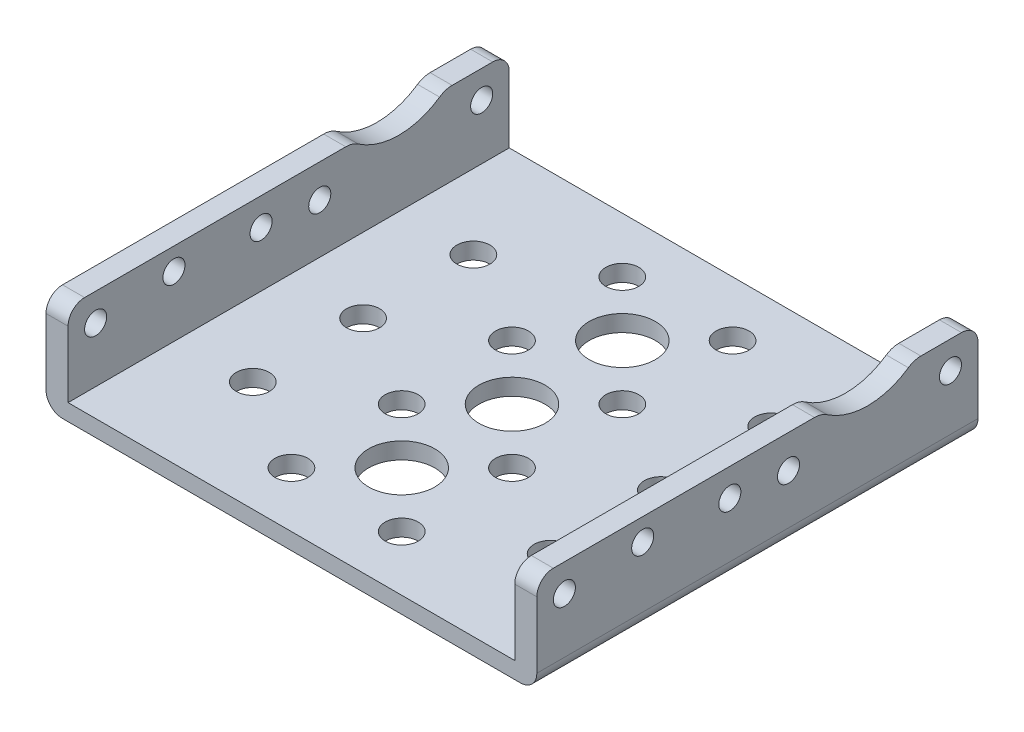
SolidWorks part; units mm, degrees
ref_plane "前视基准面" through (0, 0, 0) normal (0, 0, 1) x (1, 0, 0)
ref_plane "上视基准面" through (0, 0, 0) normal (0, 1, 0) x (1, 0, 0)
ref_plane "右视基准面" through (0, 0, 0) normal (1, 0, 0) x (0, 0, -1)
other "Configuration Table"
ref_plane "基准面1" through (0, 9, 0) normal (0, 1, 0) x (1, 0, 0)
sketch "草图1" plane through (0, 9, 0) normal (0, 1, 0) x (1, 0, 0)
  line L0 (-22.25, -20) -> (22.25, -20)
  line L1 (22.25, -20) -> (22.25, 20)
  line L2 (22.25, 20) -> (-22.25, 20)
  line L3 (-22.25, 20) -> (-22.25, -20)
  line L4 (22.25, 20) -> (-22.25, -20) construction
  line L5 (22.25, -20) -> (-22.25, 20) construction
  point P4 (0, 0)
  dimension "D1" = 44.5
  dimension "D2" = 40
extrude "凸台-拉伸1" add sketch "草图1" against normal blind 9
sketch "草图2" plane through (0, 0, -20) normal (0, 0, -1) x (-1, 0, 0)
  line L0 (20.25, 9) -> (-20.25, 9)
  line L1 (-20.25, 9) -> (-20.25, 1.5)
  line L2 (-20.25, 1.5) -> (20.25, 1.5)
  line L3 (20.25, 1.5) -> (20.25, 9)
extrude "切除-拉伸1" cut sketch "草图2" against normal through all
sketch "草图3" plane through (22.25, 0, 0) normal (1, 0, 0) x (0, 0, -1)
  line L0 (14.1533, 9) -> (5.8467, 9)
  arc A0 (5.8467, 9) -> (14.1533, 9) centre (10, 14) ccw
extrude "切除-拉伸2" cut sketch "草图3" against normal up to next
sketch "草图4" plane through (-22.25, 0, 0) normal (-1, 0, 0) x (0, 0, 1)
  line L0 (-5.8467, 9) -> (-14.1533, 9)
  arc A0 (-14.1533, 9) -> (-5.8467, 9) centre (-10, 14) ccw
extrude "切除-拉伸3" cut sketch "草图4" against normal through all
hole_wizard "Ø6.0 (6) 直径孔1" positions "草图6" profile "草图5" hole size "Ø6.0" standard "ANSI Metric"
sketch "草图6" plane through (0, 0, 0) normal (0, -1, 0) x (-1, 0, 0)
  point P0 (0, 0)
  point P1 (0, 10)
  point P2 (0, -10)
sketch "草图5" plane through (0, 0, 0) normal (1, 0, 0) x (0, 0, -1)
  line L0 (0, 0) -> (0, 9)
  line L1 (0, 9) -> (3, 9)
  line L2 (3, 9) -> (3, 0)
  line L5 (3, 0) -> (0, 0)
  line L11 (0, -6.35) -> (0, 107.95) construction
  dimension "通孔孔直径" = 6
  dimension "通孔孔深度" = 9
hole_wizard "Ø3.0 (3) 直径孔1" positions "草图8" profile "草图7" hole size "Ø3.0" standard "ANSI Metric"
sketch "草图8" plane through (0, 0, 0) normal (0, -1, 0) x (-1, 0, 0)
  point P0 (5, 5)
  point P1 (-5, 5)
  point P2 (-5, -5)
  point P3 (5, -5)
  point P4 (5, 15)
  point P5 (-5, 15)
  point P6 (-5, -15)
  point P7 (5, -15)
  point P8 (13.5, 10)
  point P9 (13.5, 0)
  point P10 (13.5, -10)
  point P11 (-13.5, 10)
  point P12 (-13.5, 0)
  point P13 (-13.5, -10)
  point P15 (0, 0)
  point P16 (0, 0)
  point P17 (0, 0)
  dimension "D1" = 13.5
  dimension "D2" = 13.5
  dimension "D3" = 10
  dimension "D4" = 10
sketch "草图7" plane through (-5, 0, -5) normal (1, 0, 0) x (0, 0, -1)
  line L0 (0, 0) -> (0, 9)
  line L1 (0, 9) -> (1.5, 9)
  line L2 (1.5, 9) -> (1.5, 0)
  line L5 (1.5, 0) -> (0, 0)
  line L11 (0, -6.35) -> (0, 107.95) construction
  dimension "通孔孔直径" = 3
  dimension "通孔孔深度" = 9
hole_wizard "Ø2.0 (2) 直径孔1" positions "草图10" profile "草图9" hole size "Ø2.0" standard "ANSI Metric"
sketch "草图10" plane through (-22.25, 0, 0) normal (-1, 0, 0) x (0, 0, 1)
  point P0 (-17.5, 6.5)
  point P1 (2.5, 6.5)
  point P2 (10.4, 7)
  point P3 (17.5, 6.5)
  point P4 (-2.82, 6)
sketch "草图9" plane through (-22.25, 6.5, -17.5) normal (0, 1, 0) x (0, 0, 1)
  line L0 (0, 0) -> (0, 2)
  line L1 (0, 2) -> (1, 2)
  line L2 (1, 2) -> (1, 0)
  line L5 (1, 0) -> (0, 0)
  line L11 (0, -6.35) -> (0, 107.95) construction
  dimension "通孔孔直径" = 2
  dimension "通孔孔深度" = 2
hole_wizard "Ø2.0 (2) 直径孔2" positions "草图12" profile "草图11" hole size "Ø2.0" standard "ANSI Metric"
sketch "草图12" plane through (22.25, 0, 0) normal (1, 0, 0) x (0, 0, -1)
  point P0 (17.5, 6.5)
  point P1 (-2.5, 6.5)
  point P2 (-10.4, 7)
  point P3 (-17.5, 6.5)
  point P4 (2.82, 6)
sketch "草图11" plane through (22.25, 6.5, -17.5) normal (0, 1, 0) x (0, 0, -1)
  line L0 (0, 0) -> (0, 44.5)
  line L1 (0, 44.5) -> (1, 44.5)
  line L2 (1, 44.5) -> (1, 0)
  line L5 (1, 0) -> (0, 0)
  line L11 (0, -6.35) -> (0, 107.95) construction
  dimension "通孔孔直径" = 2
  dimension "通孔孔深度" = 44.5
fillet "圆角1" radius 1.5 6 edges at (21.25, 9, -20) (-22.25, 0, 0) (22.25, 0, 0) (-21.25, 9, 20) (21.25, 9, 20) (-21.25, 9, -20)
fillet "圆角2" radius 2 4 edges at (-21.25, 9, -14.1533) (-21.25, 9, -5.8467) (21.25, 9, -5.8467) (21.25, 9, -14.1533)
